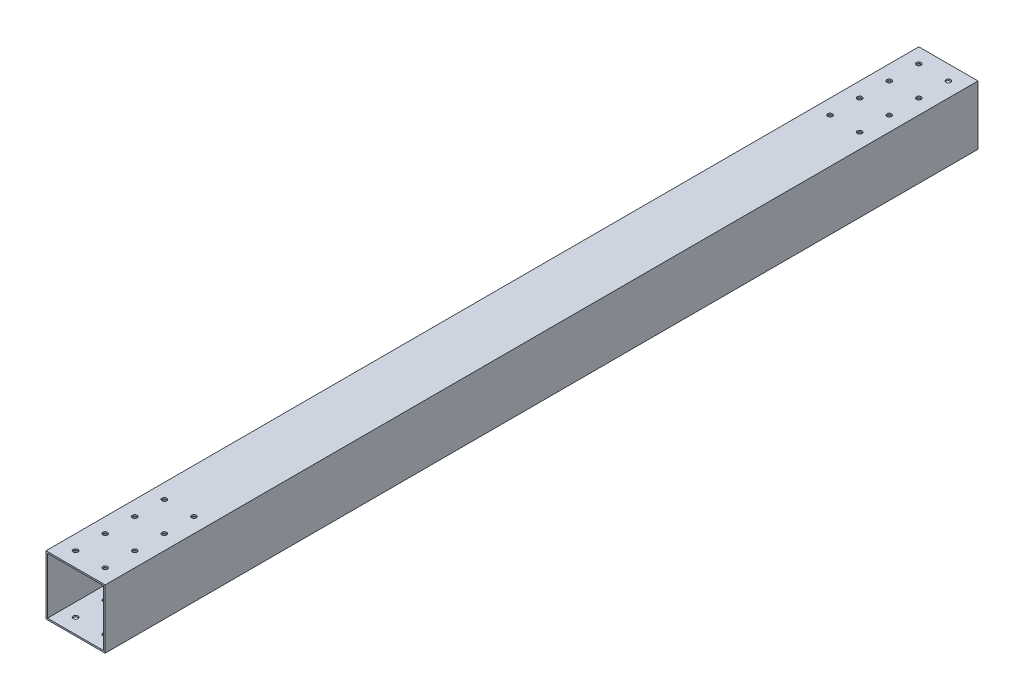
SolidWorks part; units mm, degrees
material "6061 合金"
ref_plane "前视基准面" through (0, 0, 0) normal (0, 0, 1) x (1, 0, 0)
ref_plane "上视基准面" through (0, 0, 0) normal (0, 1, 0) x (1, 0, 0)
ref_plane "右视基准面" through (0, 0, 0) normal (1, 0, 0) x (0, 0, -1)
other "Configuration Table"
sketch "草图1" plane through (0, 0, 0) normal (0, 0, 1) x (1, 0, 0)
  line L1 (-20, 20) -> (20, 20)
  line L2 (-20, 20) -> (-20, -20)
  line L3 (-20, -20) -> (20, -20)
  line L4 (20, 20) -> (20, -20)
  line L5 (-20, 20) -> (20, -20) construction
  line L6 (-20, -20) -> (20, 20) construction
  line L7 (-19, 19) -> (19, 19)
  line L8 (-19, 19) -> (-19, -19)
  line L9 (-19, -19) -> (19, -19)
  line L10 (19, 19) -> (19, -19)
  line L11 (-19, 19) -> (19, -19) construction
  line L12 (-19, -19) -> (19, 19) construction
  point P0 (0, 0)
  point P6 (0, 0)
  dimension "D1" = 40
  dimension "D2" = 1
extrude "凸台-拉伸1" add sketch "草图1" along normal mid plane 590
sketch "草图2" plane through (0, 20, 0) normal (0, 1, 0) x (1, 0, 0)
  line L0 (0, -290) -> (0, -50290) construction
  line L1 (20, -295) -> (-20, -295) construction
  line L2 (-10, -285) -> (-10, -265) construction
  line L3 (0, 0) -> (50000, 0) construction
  circle A0 centre (-10, -285) radius 1.6
  circle A1 centre (10, -285) radius 1.6
  circle A2 centre (-10, -265) radius 1.6
  circle A3 centre (10, -265) radius 1.6
  circle A4 centre (-10, -245) radius 1.6
  circle A5 centre (10, -245) radius 1.6
  circle A6 centre (-10, -225) radius 1.6
  circle A7 centre (10, -225) radius 1.6
  circle A8 centre (10, 225) radius 1.6
  circle A9 centre (-10, 225) radius 1.6
  circle A10 centre (10, 245) radius 1.6
  circle A11 centre (-10, 245) radius 1.6
  circle A12 centre (10, 265) radius 1.6
  circle A13 centre (-10, 265) radius 1.6
  circle A14 centre (10, 285) radius 1.6
  circle A15 centre (-10, 285) radius 1.6
  point P4 (0, -295)
  dimension "D1" = 20
  dimension "D2" = 3.2
  dimension "D3" = 10
  dimension "D5" = 20
  dimension "D4" = 4
extrude "切除-拉伸1" cut sketch "草图2" against normal through all
